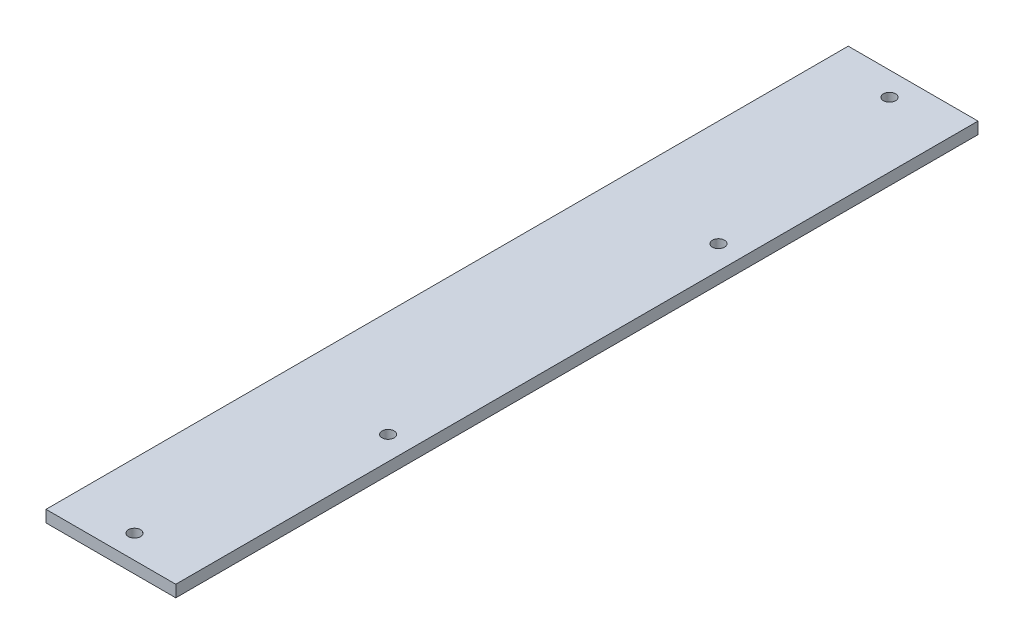
SolidWorks part; units mm, degrees
ref_plane "Front" through (0, 0, 0) normal (0, 0, 1) x (1, 0, 0)
ref_plane "Top" through (0, 0, 0) normal (0, 1, 0) x (1, 0, 0)
ref_plane "Right" through (0, 0, 0) normal (1, 0, 0) x (0, 0, -1)
sketch "Sketch1" plane through (0, 0, 0) normal (0, 1, 0) x (1, 0, 0)
  line L1 (0, 0) -> (69.85, 0)
  line L2 (0, 0) -> (0, 431.8)
  line L3 (0, 431.8) -> (69.85, 431.8)
  line L4 (69.85, 0) -> (69.85, 431.8)
  dimension "D1" = 69.85
  dimension "D2" = 431.8
extrude "Boss-Extrude1" add sketch "Sketch1" along normal blind 6.35
sketch "Sketch2" plane through (0, 6.35, 0) normal (0, 1, 0) x (1, 0, 0)
  line L0 (34.925, 431.8) -> (34.925, 0) construction
  line L1 (69.85, 431.8) -> (0, 431.8) construction
  line L2 (0, 0) -> (69.85, 0) construction
  line L3 (34.925, 0) -> (69.85, 215.9) construction
  line L4 (69.85, 0) -> (69.85, 431.8) construction
  line L5 (69.85, 215.9) -> (0, 215.9) construction
  line L6 (0, 431.8) -> (0, 0) construction
  circle A0 centre (34.925, 419.1) radius 3.2639
  circle A1 centre (57.15, 304.8) radius 3.2639
  circle A2 centre (57.15, 127) radius 3.2639
  circle A3 centre (34.925, 12.7) radius 3.2639
  dimension "D1" = 6.5278
  dimension "D2" = 12.7
  dimension "D3" = 6.5278
  dimension "D4" = 12.7
  dimension "D5" = 127
extrude "Cut-Extrude1" cut sketch "Sketch2" against normal through all
